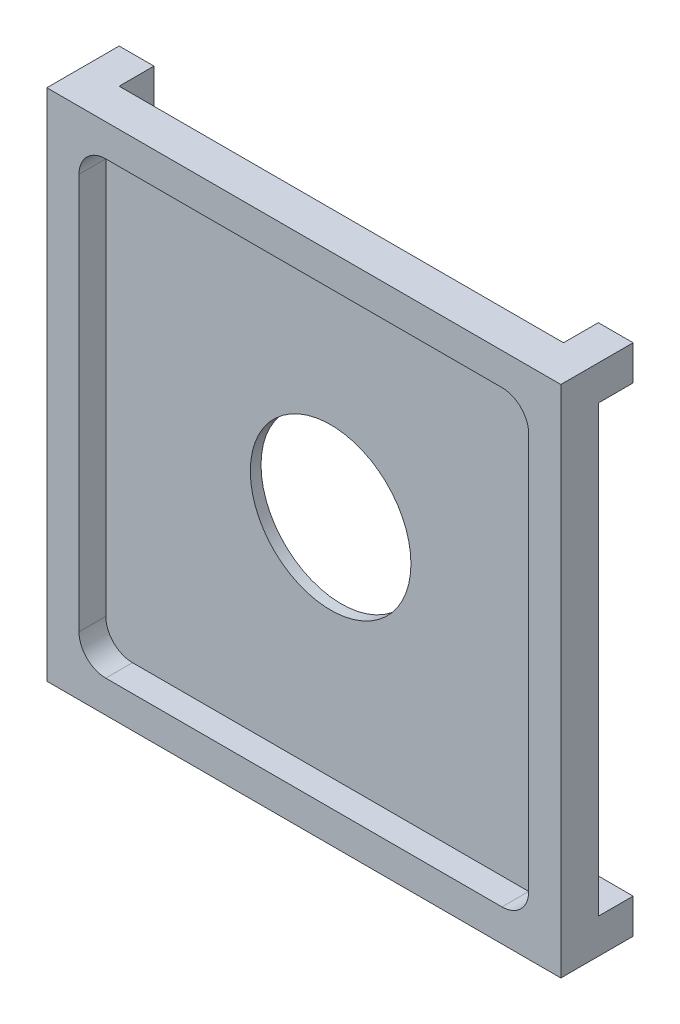
SolidWorks part; units mm, degrees
material "7075-T6 (SN)"
ref_plane "Front Plane" through (0, 0, 0) normal (0, 0, 1) x (1, 0, 0)
ref_plane "Top Plane" through (0, 0, 0) normal (0, 1, 0) x (1, 0, 0)
ref_plane "Right Plane" through (0, 0, 0) normal (1, 0, 0) x (0, 0, -1)
sketch "Sketch1" plane through (0, 0, 0) normal (0, 0, 1) x (1, 0, 0)
  line L1 (48, -48) -> (-48, -48)
  line L2 (48, -48) -> (48, 48)
  line L3 (48, 48) -> (-48, 48)
  line L4 (-48, -48) -> (-48, 48)
  line L5 (48, -48) -> (-48, 48) construction
  line L6 (48, 48) -> (-48, -48) construction
  point P0 (0, 0)
  dimension "D1" = 96
  dimension "D2" = 96
extrude "Boss-Extrude1" add sketch "Sketch1" along normal blind 2
sketch "Sketch2" plane through (0, 0, 2) normal (0, 0, 1) x (1, 0, 0)
  line L0 (48, 48) -> (-48, 48) construction
  line L1 (37, -42) -> (-37, -42)
  line L2 (42, -37) -> (42, 37)
  line L3 (37, 42) -> (-37, 42)
  line L4 (-42, -37) -> (-42, 37)
  line L5 (42, -42) -> (-42, 42) construction
  line L6 (42, 42) -> (-42, -42) construction
  line L7 (48, -48) -> (48, 48) construction
  line L12 (-48, 48) -> (-48, -48)
  line L13 (-48, -48) -> (48, -48)
  line L14 (48, -48) -> (48, 48)
  line L15 (48, 48) -> (-48, 48)
  line L16 (-48, 48) -> (-48, -48)
  line L17 (-48, -48) -> (48, -48)
  line L18 (48, -48) -> (48, 48)
  line L19 (48, 48) -> (-48, 48)
  arc A0 (-37, -42) -> (-42, -37) centre (-37, -37) cw
  arc A1 (37, -42) -> (42, -37) centre (37, -37) ccw
  arc A2 (42, 37) -> (37, 42) centre (37, 37) ccw
  arc A3 (-37, 42) -> (-42, 37) centre (-37, 37) ccw
  point P0 (0, 0)
  dimension "D4" = 5
  dimension "D1" = 6
  dimension "D2" = 6
  dimension "D3" = 0
extrude "Boss-Extrude2" add sketch "Sketch2" along normal blind 5
sketch "Sketch4" plane through (0, 0, 7) normal (0, 0, 1) x (1, 0, 0)
  line L0 (-41.5, 41.5) -> (41.5, -41.5) construction
  line L1 (-41.5, 41.5) -> (41.5, 41.5)
  line L2 (-41.5, 41.5) -> (-41.5, -41.5)
  line L3 (-41.5, -41.5) -> (41.5, -41.5)
  line L4 (41.5, 41.5) -> (41.5, -41.5)
  point P4 (0, 0)
  dimension "D1" = 83
  dimension "D2" = 83
sketch "Sketch3" plane through (0, 0, 0) normal (0, 0, -1) x (-1, 0, 0)
  line L1 (-48, 48) -> (-41.5, 48)
  line L2 (-48, 48) -> (-48, 41.5)
  line L3 (-48, 41.5) -> (-41.5, 41.5)
  line L4 (-41.5, 48) -> (-41.5, 41.5)
  line L5 (48, 48) -> (41.5, 48)
  line L6 (48, 48) -> (48, 41.5)
  line L7 (48, 41.5) -> (41.5, 41.5)
  line L8 (41.5, 48) -> (41.5, 41.5)
  line L9 (-48, -48) -> (-41.5, -48)
  line L10 (-48, -48) -> (-48, -41.5)
  line L11 (-48, -41.5) -> (-41.5, -41.5)
  line L12 (-41.5, -48) -> (-41.5, -41.5)
  line L13 (48, -48) -> (41.5, -48)
  line L14 (48, -48) -> (48, -41.5)
  line L15 (48, -41.5) -> (41.5, -41.5)
  line L16 (41.5, -48) -> (41.5, -41.5)
  dimension "D1" = 6.5
  dimension "D2" = 6.5
  dimension "D3" = 6.5
  dimension "D4" = 6.5
extrude "Boss-Extrude3" add sketch "Sketch3" along normal blind 6.5
sketch "Sketch5" plane through (0, 0, 0) normal (0, 0, -1) x (-1, 0, 0)
  circle A0 centre (0, 0) radius 15
  dimension "D1" = 30
extrude "Cut-Extrude1" cut sketch "Sketch5" against normal blind 10
equation "\"D2@Sketch1\"=\"D1@Sketch1\""
equation "\"thickness\" = 2"
equation "\"D1@Boss-Extrude1\"=\"thickness\""
equation "\"D2@Sketch2\"=\"D1@Sketch2\""
equation "\"D2@Sketch3\"=\"D1@Sketch3\""
equation "\"D3@Sketch3\"=\"D1@Sketch3\""
equation "\"D4@Sketch3\"=\"D1@Sketch3\""
equation "\"D2@Sketch4\"=\"D1@Sketch4\""
